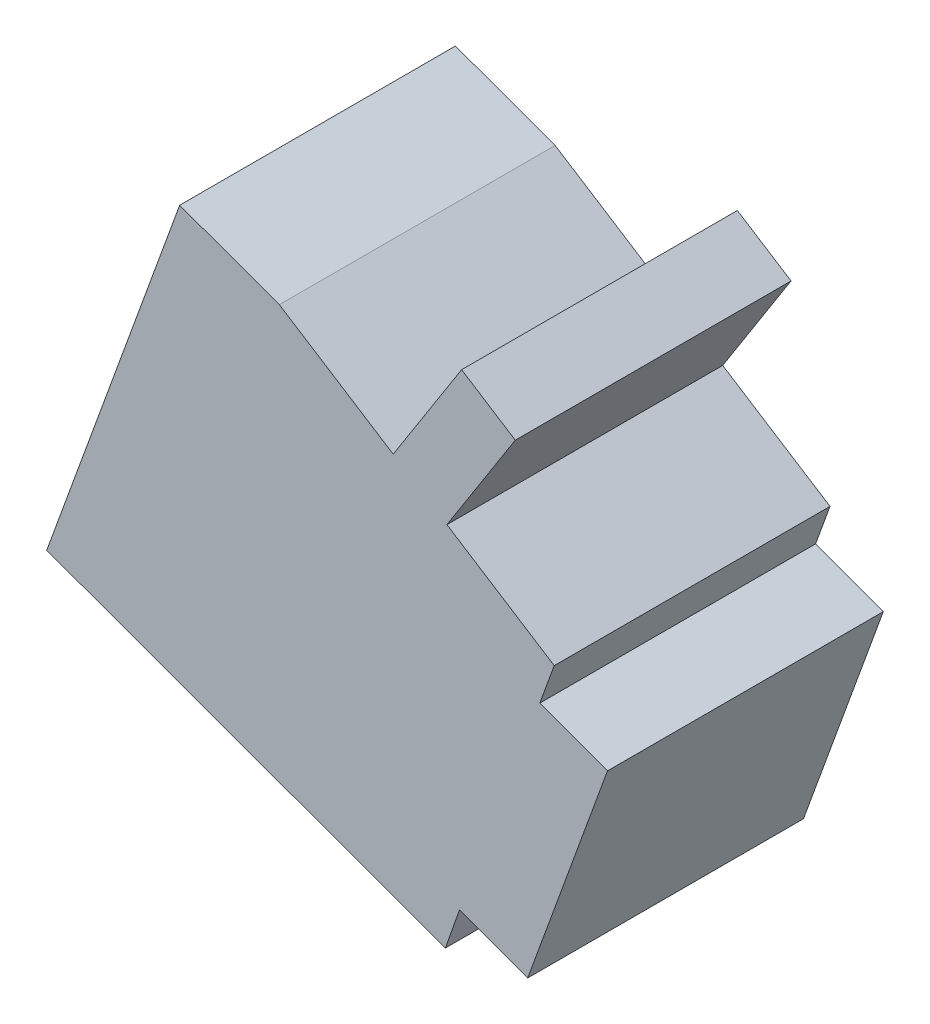
SolidWorks part; units mm, degrees
ref_plane "Plane1" through (0, 0, 0) normal (0, 0, 1) x (1, 0, 0)
ref_plane "Plane2" through (0, 0, 0) normal (0, 1, 0) x (1, 0, 0)
ref_plane "Plane3" through (0, 0, 0) normal (1, 0, 0) x (0, 0, -1)
sketch "Sketch1" plane through (0, 0, 0) normal (0, 0, 1) x (1, 0, 0)
  line L1 (0, 0) -> (203.2, 0)
  line L2 (0, 0) -> (0, 101.6)
  line L3 (0, 101.6) -> (203.2, 101.6)
  line L4 (203.2, 0) -> (203.2, 101.6)
  dimension "D1" = 203.2
  dimension "D2" = 101.6
extrude "Extrude1" add sketch "Sketch1" along normal blind 50.8
sketch "Sketch2" plane through (0, 0, 50.8) normal (0, 0, 1) x (1, 0, 0)
  line L0 (83.0232, 99.06) -> (89.3732, 99.06)
  line L2 (157.48, 83.82) -> (157.48, 78.74)
  line L3 (157.48, 78.74) -> (91.44, 78.74)
  line L4 (91.44, 78.74) -> (83.0232, 99.06)
  line L5 (203.2, 101.6) -> (0, 101.6) construction
  line L6 (0, 101.6) -> (0, 0) construction
  line L7 (157.48, 83.82) -> (102.4931, 88.7077)
  line L8 (98.7377, 90.3765) -> (89.3732, 99.06)
  arc A0 (98.7377, 90.3765) -> (102.4931, 88.7077) centre (103.0553, 95.0328) ccw
  point P12 (100.33, 88.9)
  dimension "D10" = 6.35
  dimension "D1" = 67.5
  dimension "D2" = 20.32
  dimension "D3" = 2.54
  dimension "D4" = 5.08
  dimension "D5" = 66.04
  dimension "D6" = 157.48
  dimension "D7" = 6.35
  dimension "D8" = 57.15
  dimension "D9" = 5.08
sketch "Sketch4" plane through (0, 0, 50.8) normal (0, 0, 1) x (1, 0, 0)
  line L0 (86.5799, 90.4733) -> (72.5, 84.6412)
  line L1 (91.44, 78.74) -> (83.0232, 99.06) construction
  line L2 (72.5, 84.6412) -> (69.6673, 84.8425)
  line L3 (69.6673, 84.8425) -> (73.0694, 76.6292)
  line L4 (73.0694, 76.6292) -> (74.93, 78.7745)
  line L5 (74.93, 78.7745) -> (89.01, 84.6066)
  line L6 (89.01, 84.6066) -> (91.8426, 84.4053)
  line L7 (91.8426, 84.4053) -> (88.4406, 92.6186)
  line L8 (88.4406, 92.6186) -> (86.5799, 90.4733)
  line L9 (79.54, 87.5572) -> (81.97, 81.6906)
  dimension "D1" = 6.35
  dimension "D2" = 8.89
  dimension "D3" = 1.27
  dimension "D4" = 8.89
  dimension "D5" = 1.27
  dimension "D6" = 2.54
  dimension "D7" = 2.54
  dimension "D8" = 15.24
  dimension "D9" = 6.35
sketch "Sketch5" plane through (0, 0, 50.8) normal (0, 0, 1) x (1, 0, 0)
  line L0 (69.7842, 91.1978) -> (77.5603, 72.4245)
  line L1 (77.5603, 72.4245) -> (43.4353, 38.2996)
  line L2 (43.4353, 38.2996) -> (23.4233, 51.0486)
  line L5 (23.4233, 51.0486) -> (30.1436, 56.8684)
  line L6 (157.48, 78.74) -> (91.44, 78.74) construction
  line L7 (30.1436, 56.8684) -> (37.6275, 52.1007)
  line L8 (45.5295, 52.9661) -> (64.4212, 71.8578)
  line L9 (65.7977, 78.778) -> (63.0639, 85.3779)
  line L10 (63.0639, 85.3779) -> (69.7842, 91.1978)
  arc A0 (37.6275, 52.1007) -> (45.5295, 52.9661) centre (41.0393, 57.4562) ccw
  arc A1 (65.7977, 78.778) -> (64.4212, 71.8578) centre (59.9311, 76.3479) cw
  point P14 (41.9258, 49.3624)
  dimension "D10" = 6.35
  dimension "D1" = 135
  dimension "D2" = 6.35
  dimension "D3" = 8.89
  dimension "D4" = 48.26
  dimension "D5" = 102.5
  dimension "D6" = 8.89
  dimension "D7" = 20.32
  dimension "D8" = 8.89
  dimension "D9" = 13.97
sketch "Sketch6" plane through (0, 0, 50.8) normal (0, 0, 1) x (1, 0, 0)
  line L0 (31.6531, 45.8056) -> (23.4647, 32.9524)
  line L1 (43.4353, 38.2996) -> (23.4233, 51.0486) construction
  line L2 (23.4647, 32.9524) -> (21.0288, 31.4925)
  line L3 (21.0288, 31.4925) -> (26.3844, 28.0807)
  line L4 (26.3844, 28.0807) -> (26.678, 30.9052)
  line L5 (26.678, 30.9052) -> (34.8665, 43.7585)
  line L6 (34.8665, 43.7585) -> (37.3023, 45.2184)
  line L7 (37.3023, 45.2184) -> (31.9468, 48.6302)
  line L8 (30.7722, 37.3319) -> (27.5589, 39.379)
  line L9 (31.9468, 48.6302) -> (31.6531, 45.8056)
  dimension "D1" = 3.81
  dimension "D2" = 6.35
  dimension "D3" = 6.35
  dimension "D4" = 1.27
  dimension "D5" = 1.27
  dimension "D6" = 2.54
  dimension "D7" = 2.54
  dimension "D8" = 15.24
  dimension "D9" = 10.16
sketch "Sketch8" plane through (0, 0, 50.8) normal (0, 0, 1) x (1, 0, 0)
  line L0 (16.648, 37.2951) -> (33.1047, 26.811)
  line L1 (33.1047, 26.811) -> (26.5892, 8.9099)
  line L2 (26.5892, 8.9099) -> (2.721, 17.5972)
  line L3 (16.648, 37.2951) -> (10.6809, 39.4669)
  line L4 (2.721, 17.5972) -> (10.6809, 39.4669)
  line L8 (43.4353, 38.2996) -> (23.4233, 51.0486) construction
  dimension "D1" = 7.62
  dimension "D2" = 102.5
  dimension "D3" = 25.4
  dimension "D4" = 19.05
  dimension "D5" = 6.35
sketch "Sketch14" plane through (0, 0, 50.8) normal (0, 0, 1) x (1, 0, 0)
  line L0 (157.48, 78.74) -> (91.44, 78.74) construction
  line L1 (93.98, 80.772) -> (154.94, 80.772)
  line L2 (93.98, 80.772) -> (93.98, 74.422)
  line L3 (93.98, 74.422) -> (154.94, 74.422)
  line L4 (154.94, 80.772) -> (154.94, 74.422)
  line L5 (157.48, 83.82) -> (157.48, 78.74) construction
  dimension "D1" = 2.032
  dimension "D2" = 2.54
  dimension "D3" = 2.54
  dimension "D4" = 6.35
sketch "Sketch15" plane through (0, 0, 50.8) normal (0, 0, 1) x (1, 0, 0)
  line L0 (43.7945, 41.5325) -> (48.2847, 37.0423)
  line L2 (48.2847, 37.0423) -> (78.8175, 67.5752)
  line L3 (78.8175, 67.5752) -> (74.3274, 72.0653)
  line L4 (74.3274, 72.0653) -> (43.7945, 41.5325)
  line L5 (77.5603, 72.4245) -> (43.4353, 38.2996) construction
  dimension "D1" = 2.032
  dimension "D2" = 2.54
  dimension "D3" = 6.35
  dimension "D4" = 2.54
sketch "Sketch16" plane through (0, 0, 50.8) normal (0, 0, 1) x (1, 0, 0)
  line L0 (25.5485, 11.9917) -> (31.5155, 9.8199)
  line L1 (31.5155, 9.8199) -> (36.2935, 22.9474)
  line L2 (36.2935, 22.9474) -> (30.3265, 25.1192)
  line L3 (30.3265, 25.1192) -> (25.5485, 11.9917)
  line L4 (33.1047, 26.811) -> (26.5892, 8.9099) construction
  dimension "D1" = 2.032
  dimension "D2" = 6.35
  dimension "D3" = 2.54
  dimension "D4" = 2.54
sketch "Sketch19" plane through (0, 0, 50.8) normal (0, 0, 1) x (1, 0, 0)
  line L0 (155.194, 72.39) -> (86.506, 72.39)
  line L1 (86.506, 72.39) -> (45.2314, 31.1154)
  line L2 (45.2314, 31.1154) -> (113.9194, 31.1154)
  line L3 (113.9194, 31.1154) -> (155.194, 72.39)
  line L4 (93.98, 74.422) -> (154.94, 74.422) construction
  line L5 (48.2847, 37.0423) -> (78.8175, 67.5752) construction
  line L7 (43.7945, 41.5325) -> (48.2847, 37.0423) construction
  line L8 (154.94, 80.772) -> (154.94, 74.422) construction
  dimension "D1" = 2.032
  dimension "D2" = 2.032
  dimension "D3" = 6.35
  dimension "D4" = 0.254
sketch "Sketch21" plane through (0, 0, 50.8) normal (0, 0, 1) x (1, 0, 0)
  line L0 (10.6809, 39.4669) -> (16.648, 37.2951)
  line L1 (16.648, 37.2951) -> (23.4647, 32.9524)
  line L2 (23.4647, 32.9524) -> (27.5589, 39.379)
  line L3 (27.5589, 39.379) -> (30.7722, 37.3319)
  line L4 (30.7722, 37.3319) -> (26.678, 30.9052)
  line L5 (26.678, 30.9052) -> (33.1047, 26.811)
  line L6 (33.1047, 26.811) -> (32.239, 24.4326)
  line L7 (32.239, 24.4326) -> (36.2935, 22.9474)
  line L8 (36.2935, 22.9474) -> (31.5155, 9.8199)
  line L9 (31.5155, 9.8199) -> (27.4308, 11.3066)
  line L10 (27.4308, 11.3066) -> (26.5892, 8.9099)
  line L11 (26.5892, 8.9099) -> (2.721, 17.5972)
  line L12 (2.721, 17.5972) -> (10.6809, 39.4669)
extrude "Extrude2" add sketch "Sketch21" along normal blind 16.51
sketch "Sketch23" plane through (0, 0, 0) normal (0, -1, 0) x (1, 0, 0)
  line L0 (0, 50.8) -> (0, 0)
  line L1 (0, 50.8) -> (203.2, 50.8) construction
  line L2 (0, 0) -> (203.2, 0)
  line L3 (203.2, 0) -> (203.2, 50.8)
  line L4 (203.2, 50.8) -> (203.2, 0) construction
  line L5 (203.2, 50.8) -> (0, 50.8)
extrude "Extrude3" cut sketch "Sketch23" against normal blind 508
